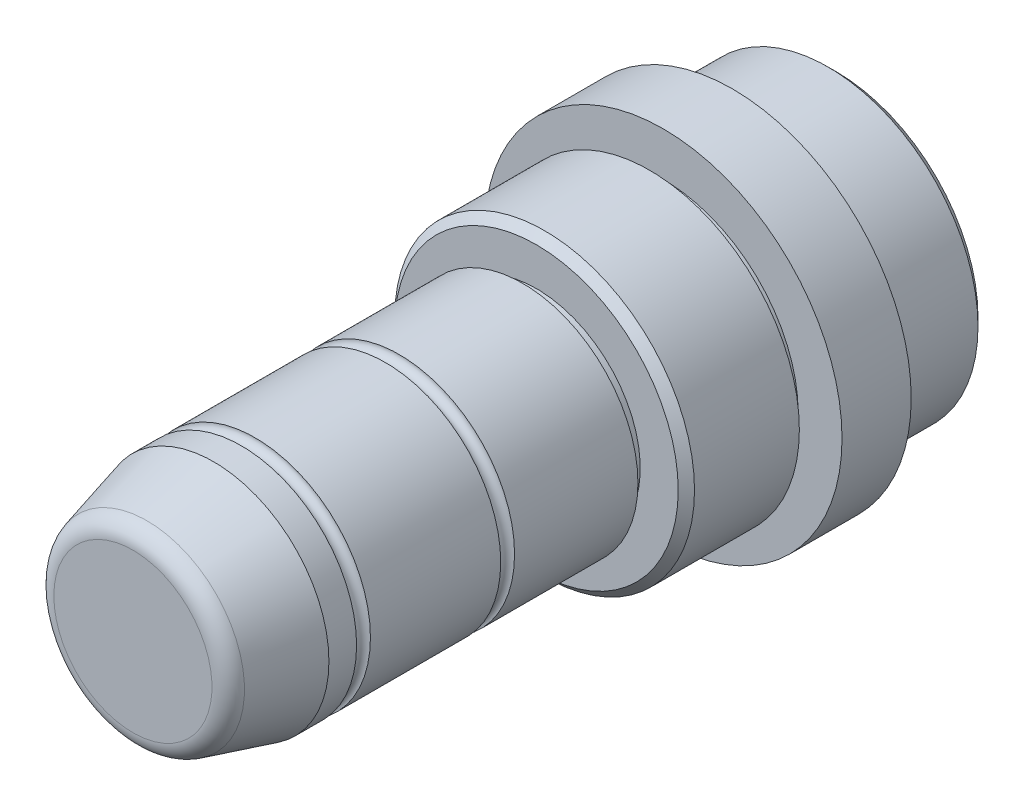
SolidWorks part; units mm, degrees
ref_plane "Спереди" through (0, 0, 0) normal (0, 0, 1) x (1, 0, 0)
ref_plane "Сверху" through (0, 0, 0) normal (0, 1, 0) x (1, 0, 0)
ref_plane "Справа" through (0, 0, 0) normal (1, 0, 0) x (0, 0, -1)
ref_plane "Плоскость4" through (0, 0, 0) normal (0, -1, 0) x (1, 0, 0)
sketch "Эскиз1" plane through (0, 0, 0) normal (0, -1, 0) x (1, 0, 0)
  line L0 (6.8583, 61) -> (0, 61)
  line L1 (0, 61) -> (0, 0)
  line L2 (0, 0) -> (12.2929, 0)
  line L3 (12.2929, 0) -> (13, 0.7071)
  line L4 (13, 0.7071) -> (13, 7.8)
  line L5 (13, 7.8) -> (11.7, 7.8)
  line L6 (11.7, 7.8) -> (11.7, 9)
  line L7 (11.7, 9) -> (15.5, 9)
  line L8 (15.5, 9) -> (15.5, 15)
  line L9 (15.5, 15) -> (11.7, 15)
  line L10 (11.7, 15) -> (11.7, 16.2)
  line L11 (11.7, 16.2) -> (13, 16.2)
  line L12 (13, 16.2) -> (13, 25.2929)
  line L13 (13, 25.2929) -> (12.2929, 26)
  line L14 (12.2929, 26) -> (9, 26)
  line L15 (9, 26) -> (9, 27.2)
  line L16 (9, 27.2) -> (10, 27.2)
  line L17 (10, 27.2) -> (10, 37.9)
  line L18 (10, 39.1) -> (10, 50.4)
  line L19 (10, 51.6) -> (10, 54)
  line L20 (10, 54) -> (8.452, 59.7771)
  line L21 (0, 61.005) -> (0, -0.005) construction
  arc A0 (10, 37.9) -> (10, 39.1) centre (10, 38.5) cw
  arc A1 (10, 50.4) -> (10, 51.6) centre (10, 51) cw
  arc A2 (8.452, 59.7771) -> (6.8583, 61) centre (6.8583, 59.35) ccw
revolve "Повернуть1" add sketch "Эскиз1" angle 360 about L21
